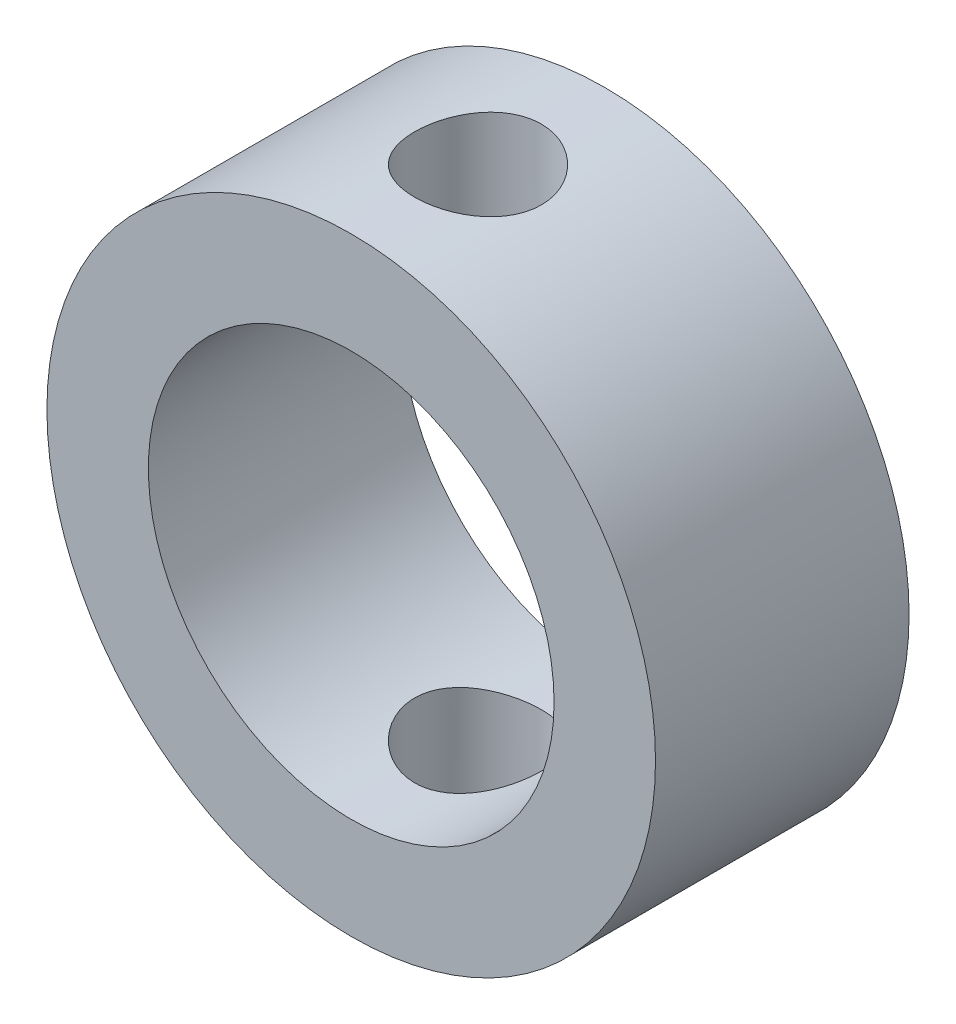
SolidWorks part; units mm, degrees
ref_plane "前视基准面" through (0, 0, 0) normal (0, 0, 1) x (1, 0, 0)
ref_plane "上视基准面" through (0, 0, 0) normal (0, 1, 0) x (1, 0, 0)
ref_plane "右视基准面" through (0, 0, 0) normal (1, 0, 0) x (0, 0, -1)
sketch "草图1" plane through (0, 0, 0) normal (0, 0, 1) x (1, 0, 0)
  circle A0 centre (0, 0) radius 6
  circle A1 centre (0, 0) radius 4
  dimension "D1" = 8
  dimension "D2" = 12
extrude "凸台-拉伸1" add sketch "草图1" along normal blind 5
sketch "草图2" plane through (0, 0, 0) normal (0, 1, 0) x (1, 0, 0)
  line L0 (0, 0) -> (0, -5) construction
  line L1 (-6, -5) -> (6, -5) construction
  line L2 (6, -2.5) -> (-6, -2.5) construction
  line L3 (6, -5) -> (6, 0) construction
  line L4 (-6, 0) -> (-6, -5) construction
  circle A1 centre (0, -2.5) radius 1.25
  dimension "D1" = 2.5
extrude "切除-拉伸1" cut sketch "草图2" against normal up to next and the other way up to next
